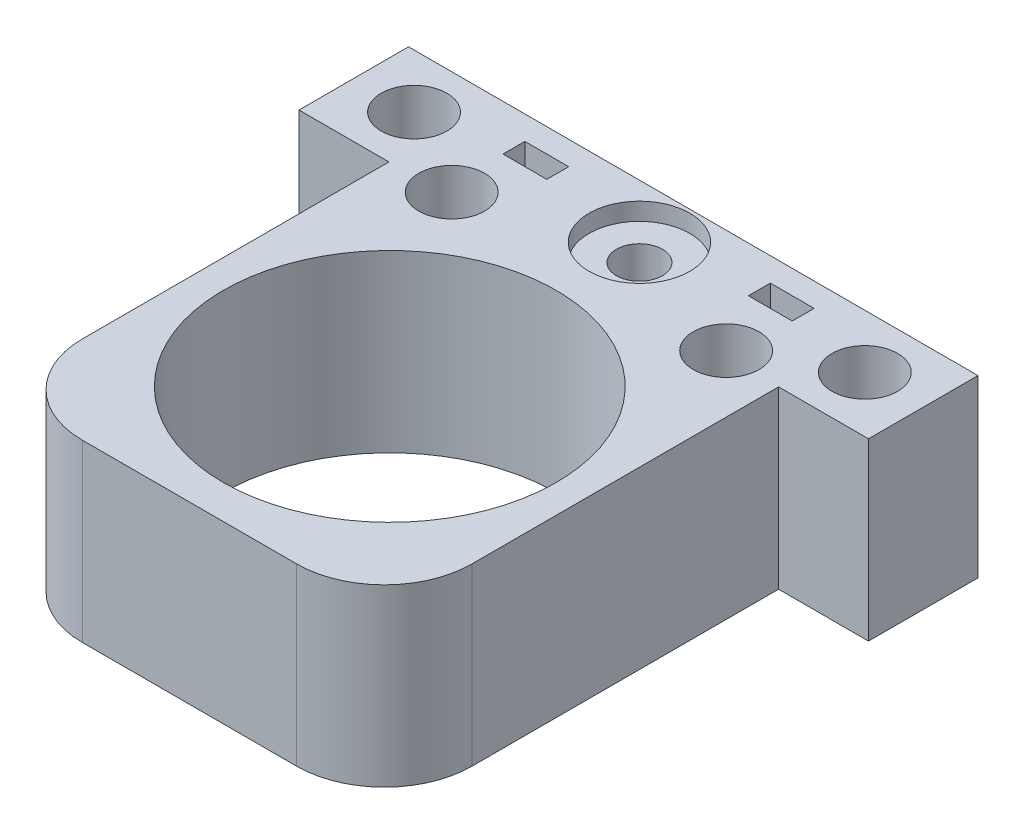
SolidWorks part; units mm, degrees
ref_plane "Front Plane" through (0, 0, 0) normal (0, 0, 1) x (1, 0, 0)
ref_plane "Top Plane" through (0, 0, 0) normal (0, 1, 0) x (1, 0, 0)
ref_plane "Right Plane" through (0, 0, 0) normal (1, 0, 0) x (0, 0, -1)
sketch "Sketch1" plane through (0, 0, 0) normal (0, 1, 0) x (1, 0, 0)
  line L0 (0, 0) -> (0, -45) construction
  line L1 (-65, 25) -> (65, 25)
  line L2 (-65, 25) -> (-65, -25)
  line L3 (-65, -25) -> (-32.8976, -25)
  line L4 (65, 25) -> (65, -25)
  line L5 (-65, 25) -> (65, -25) construction
  line L6 (-65, -25) -> (65, 25) construction
  line L7 (32.8976, -25) -> (65, -25)
  arc A0 (32.8976, -25) -> (-32.8976, -25) centre (0, -45) ccw
  point P0 (0, 0)
  dimension "D4" = 77
  dimension "D1" = 50
  dimension "D2" = 130
  dimension "D3" = 45
extrude "Boss-Extrude1" add sketch "Sketch1" along normal blind 60
sketch "Sketch2" plane through (0, 60, 0) normal (0, 1, 0) x (1, 0, 0)
  line L0 (0, -6.5) -> (0, 25) construction
  line L1 (65, 25) -> (-65, 25) construction
  circle A0 centre (-51.4526, 12.7142) radius 7.5
  arc A1 (32.8976, -25) -> (-32.8976, -25) centre (0, -45) ccw construction
  circle A2 centre (51.4526, 12.7142) radius 7.5
  dimension "D1" = 15
extrude "Cut-Extrude1" cut sketch "Sketch2" against normal blind 60
sketch "Sketch3" plane through (0, 60, 0) normal (0, 1, 0) x (1, 0, 0)
  line L0 (0, -6.5) -> (0, 25) construction
  line L1 (65, 25) -> (-65, 25) construction
  line L2 (-51.4526, 12.7142) -> (51.4526, 12.7142) construction
  arc A0 (32.8976, -25) -> (-32.8976, -25) centre (0, -45) ccw construction
  circle A1 centre (0, 12.7142) radius 5.25
  dimension "D1" = 10.5
extrude "Cut-Extrude2" cut sketch "Sketch3" against normal blind 60
sketch "Sketch4" plane through (0, 60, 0) normal (0, 1, 0) x (1, 0, 0)
  circle A0 centre (0, 12.7142) radius 11.5
  dimension "D1" = 23
extrude "Cut-Extrude3" cut sketch "Sketch4" against normal blind 4
sketch "Sketch5" plane through (0, 60, 0) normal (0, 1, 0) x (1, 0, 0)
  line L0 (0, 25) -> (0, -6.5) construction
  line L1 (-57.8842, -14.0803) -> (-47.8842, -14.0803)
  line L2 (-57.8842, -14.0803) -> (-57.8842, -19.0803)
  line L3 (-57.8842, -19.0803) -> (-47.8842, -19.0803)
  line L4 (-47.8842, -14.0803) -> (-47.8842, -19.0803)
  line L5 (65, 25) -> (-65, 25) construction
  line L6 (-33.0131, 19.5794) -> (-23.0131, 19.5794)
  line L7 (-33.0131, 19.5794) -> (-33.0131, 14.5794)
  line L8 (-33.0131, 14.5794) -> (-23.0131, 14.5794)
  line L9 (-23.0131, 19.5794) -> (-23.0131, 14.5794)
  line L10 (57.8842, -19.0803) -> (47.8842, -19.0803)
  line L11 (47.8842, -14.0803) -> (47.8842, -19.0803)
  line L12 (57.8842, -14.0803) -> (47.8842, -14.0803)
  line L13 (57.8842, -14.0803) -> (57.8842, -19.0803)
  line L14 (33.0131, 19.5794) -> (33.0131, 14.5794)
  line L15 (33.0131, 14.5794) -> (23.0131, 14.5794)
  line L16 (23.0131, 19.5794) -> (23.0131, 14.5794)
  line L17 (33.0131, 19.5794) -> (23.0131, 19.5794)
  arc A0 (32.8976, -25) -> (-32.8976, -25) centre (0, -45) ccw construction
  dimension "D1" = 5
  dimension "D2" = 10
extrude "Cut-Extrude4" cut sketch "Sketch5" against normal blind 60
sketch "Sketch6" plane through (0, 60, 0) normal (0, 1, 0) x (1, 0, 0)
  line L0 (-65, 25) -> (-65, -25) construction
  line L1 (-65, 0) -> (65, 0)
  line L2 (-65, 0) -> (-65, -90)
  line L3 (-65, -90) -> (65, -90)
  line L4 (65, 0) -> (65, -90)
  dimension "D1" = 90
extrude "Boss-Extrude2" add sketch "Sketch6" against normal blind 60
sketch "Sketch7" plane through (0, 60, 0) normal (0, 1, 0) x (1, 0, 0)
  line L0 (0, 12.7142) -> (0, -44.2858) construction
  circle A0 centre (0, -44.2858) radius 38
  dimension "D2" = 76
  dimension "D1" = 57
extrude "Cut-Extrude5" cut sketch "Sketch7" against normal blind 60
sketch "Sketch8" plane through (0, 0, 0) normal (0, -1, 0) x (1, 0, 0)
  line L1 (-65, 90) -> (65, 90)
  line L2 (-65, 90) -> (-65, -25)
  line L3 (-65, -25) -> (65, -25)
  line L4 (65, 90) -> (65, -25)
extrude "Cut-Extrude6" cut sketch "Sketch8" against normal blind 20
sketch "Sketch9" plane through (0, 60, 0) normal (0, 1, 0) x (1, 0, 0)
  line L0 (-65, 25) -> (-65, -90) construction
  line L1 (-65, 0) -> (-44.4744, 0)
  line L2 (-65, 0) -> (-65, -90)
  line L3 (-65, -90) -> (-44.4744, -90)
  line L4 (-44.4744, 0) -> (-44.4744, -90)
  line L5 (-65, -90) -> (65, -90) construction
  line L6 (0, 12.7142) -> (0, -90) construction
  line L7 (65, -90) -> (44.4744, -90)
  line L8 (44.4744, 0) -> (44.4744, -90)
  line L9 (65, 0) -> (44.4744, 0)
  line L10 (65, 0) -> (65, -90)
extrude "Cut-Extrude7" cut sketch "Sketch9" against normal blind 45
fillet "Fillet2" radius 20 2 edges at (44.4744, 40, 90) (-44.4744, 40, 90)
sketch "Sketch10" plane through (0, 60, 0) normal (0, 1, 0) x (1, 0, 0)
  line L0 (0, 12.7142) -> (0, -36.1521) construction
  circle A0 centre (-51.4526, 12.7142) radius 7.5
  circle A1 centre (-31.3268, 1.1804) radius 7.5
  circle A2 centre (31.3268, 1.1804) radius 7.5
extrude "Cut-Extrude8" cut sketch "Sketch10" against normal blind 40
